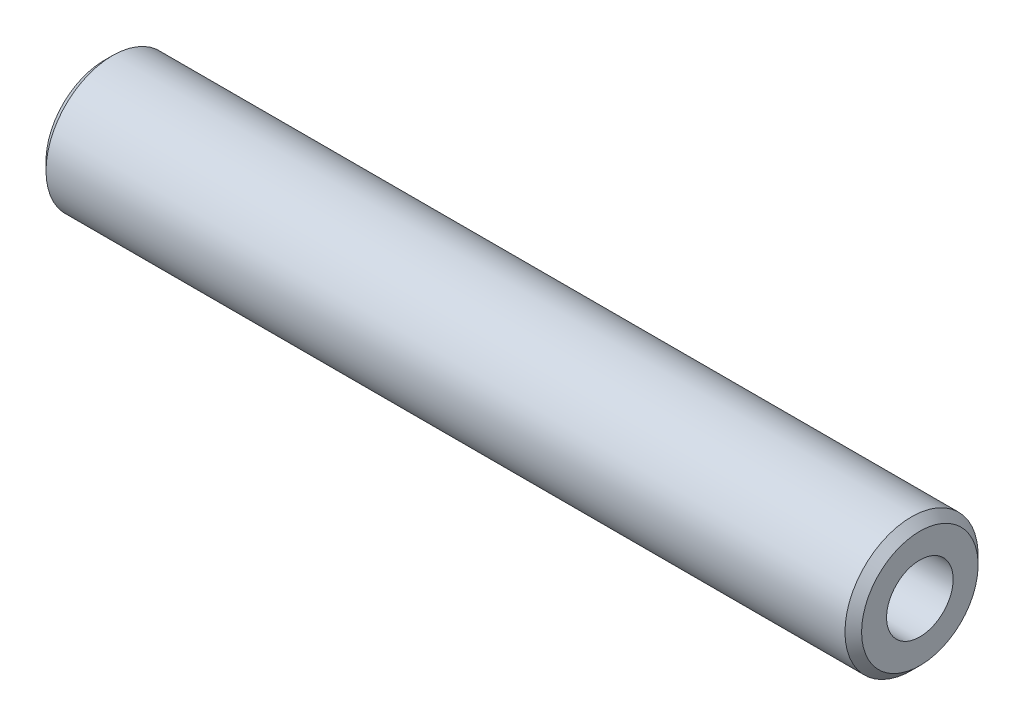
SolidWorks part; units mm, degrees
material "1.4301 (X5CrNi18-10)"
ref_plane "正面" through (0, 0, 0) normal (0, 0, 1) x (1, 0, 0)
ref_plane "平面" through (0, 0, 0) normal (0, 1, 0) x (1, 0, 0)
ref_plane "右側面" through (0, 0, 0) normal (1, 0, 0) x (0, 0, -1)
sketch "ｽｹｯﾁ1" plane through (0, 0, 0) normal (0, 0, 1) x (1, 0, 0)
  line L0 (0, 0) -> (21203.2319, 0) construction
  line L2 (-24.5, 0) -> (24.5, 0)
  line L3 (-24.5, 0) -> (-24.5, 4)
  line L4 (-24.5, 4) -> (24.5, 4)
  line L5 (24.5, 0) -> (24.5, 4)
  point P7 (0, 0)
  dimension "D1" = 8
  dimension "D2" = 49
revolve "回転1" add sketch "ｽｹｯﾁ1" angle 360 about L0
hole_wizard "M4x0.7 ねじ穴1" positions "3Dｽｹｯﾁ1" profile "ｽｹｯﾁ3" tap size "M4x0.7" standard "JIS"
sketch3d "3Dｽｹｯﾁ1"
  line L0 (24.5, 0, 0) -> (-24.5, 0, 0) construction
  point P0 (24.5, 0, 0)
  point P4 (-24.5, 0, 0)
sketch "ｽｹｯﾁ3" plane through (24.5, 0, 0) normal (0, 1, 0) x (0, 0, -1)
  line L0 (0, 0) -> (0, 12.4914)
  line L1 (0, 12.4914) -> (1.65, 11.5)
  line L2 (1.65, 11.5) -> (1.65, 8)
  line L3 (1.65, 8) -> (2, 8)
  line L4 (2, 8) -> (2, 0)
  line L5 (2, 0) -> (0, 0)
  line L10 (0, 12.4914) -> (-1.65, 11.5) construction
  line L11 (0, -6.35) -> (0, 107.95) construction
  dimension "ねじ下穴ﾄﾞﾘﾙ直径" = 3.3
  dimension "ねじ下穴ﾄﾞﾘﾙの深さ" = 11.5
  dimension "ねじ山の主要直径" = 4
  dimension "ねじ山の深さ" = 8
  dimension "ﾄﾞﾘﾙ角度" = 118
chamfer "面取り1" distance 0.5 angle 45 2 edges at (-24.5, 0, 4) (24.5, 0, 4)
